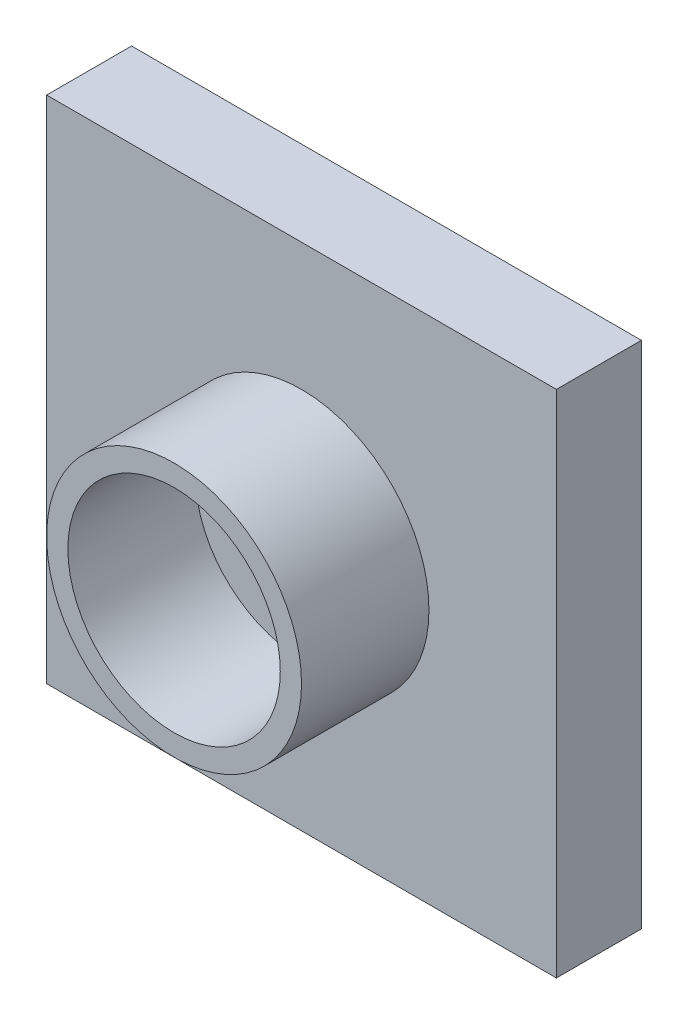
SolidWorks part; units mm, degrees
material "PE High Density"
ref_plane "Front Plane" through (0, 0, 0) normal (0, 0, 1) x (1, 0, 0)
ref_plane "Top Plane" through (0, 0, 0) normal (0, 1, 0) x (1, 0, 0)
ref_plane "Right Plane" through (0, 0, 0) normal (1, 0, 0) x (0, 0, -1)
sketch "Sketch1" plane through (0, 0, 0) normal (0, 0, 1) x (1, 0, 0)
  line L1 (-6, 6) -> (6, 6)
  line L2 (-6, 6) -> (-6, -6)
  line L3 (-6, -6) -> (6, -6)
  line L4 (6, 6) -> (6, -6)
  line L5 (-6, 6) -> (6, -6) construction
  line L6 (-6, -6) -> (6, 6) construction
  point P0 (0, 0)
  dimension "D1" = 12
  dimension "D2" = 12
extrude "Boss-Extrude1" add sketch "Sketch1" along normal blind 2
sketch "Sketch2" plane through (0, 0, 2) normal (0, 0, 1) x (1, 0, 0)
  circle A1 centre (0, 0) radius 2.5
  circle A2 centre (0, 0) radius 3
  dimension "D1" = 6
  dimension "D2" = 5
extrude "Boss-Extrude2" add sketch "Sketch2" along normal blind 3
sketch "Sketch5" plane through (0, 0, 2) normal (0, 0, 1) x (1, 0, 0)
  circle A0 centre (0, 0) radius 1
  dimension "D1" = 2
extrude "Cut-Extrude1" cut sketch "Sketch5" against normal through all
